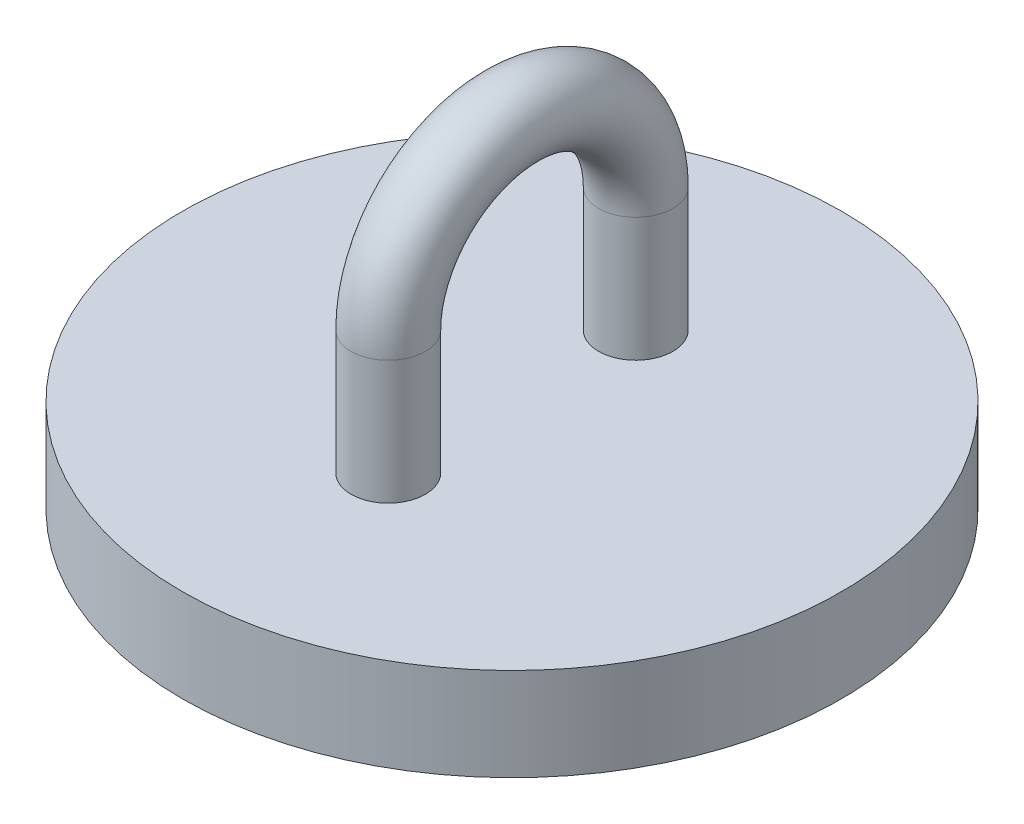
SolidWorks part; units mm, degrees
ref_plane "Front Plane" through (0, 0, 0) normal (0, 0, 1) x (1, 0, 0)
ref_plane "Top Plane" through (0, 0, 0) normal (0, 1, 0) x (1, 0, 0)
ref_plane "Right Plane" through (0, 0, 0) normal (1, 0, 0) x (0, 0, -1)
sketch "Sketch1" plane through (0, 0, 0) normal (0, 1, 0) x (1, 0, 0)
  circle A0 centre (0, 0) radius 10.65
  dimension "D1" = 21.3
extrude "Boss-Extrude1" add sketch "Sketch1" along normal blind 3
sketch "Sketch2" plane through (0, 3, 0) normal (0, 1, 0) x (1, 0, 0)
  line L0 (0, -4) -> (0, 0)
  circle A0 centre (0, -4) radius 1.2
  dimension "D1" = 2.4
  dimension "D2" = 4
sketch "Sketch3" plane through (0, 0, 0) normal (1, 0, 0) x (0, 0, -1)
  line L0 (-4, 3) -> (-4, 7)
  line L1 (-2.8, 3) -> (-5.2, 3) construction
  line L2 (4, 7) -> (4, 3)
  line L3 (10.65, 3) -> (-10.65, 3) construction
  arc A0 (4, 7) -> (-4, 7) centre (0, 7) ccw
  dimension "D1" = 4
  dimension "D2" = 4
sweep "Sweep1" add profiles "Sketch2" path "Sketch3"
